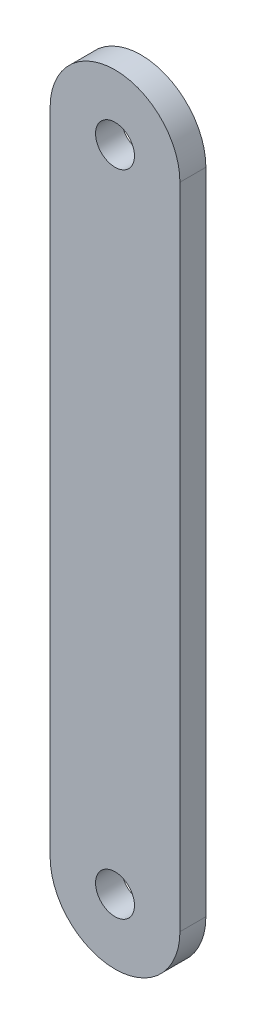
SolidWorks part; units mm, degrees
ref_plane "前视基准面" through (0, 0, 0) normal (0, 0, 1) x (1, 0, 0)
ref_plane "上视基准面" through (0, 0, 0) normal (0, 1, 0) x (1, 0, 0)
ref_plane "右视基准面" through (0, 0, 0) normal (1, 0, 0) x (0, 0, -1)
sketch "草图1" plane through (0, 0, 0) normal (0, 0, 1) x (1, 0, 0)
  line L0 (0, -25) -> (0, 25) construction
  line L1 (-5, -25) -> (-5, 25)
  line L2 (5, -25) -> (5, 25)
  arc A0 (-5, -25) -> (5, -25) centre (0, -25) ccw
  arc A1 (5, 25) -> (-5, 25) centre (0, 25) ccw
  circle A2 centre (0, 25) radius 1.5
  circle A3 centre (0, -25) radius 1.5
  point P2 (0, 0)
  dimension "D2" = 3
  dimension "D3" = 3
  dimension "D1" = 50
  dimension "D4" = 10
extrude "凸台-拉伸1" add sketch "草图1" along normal blind 2
